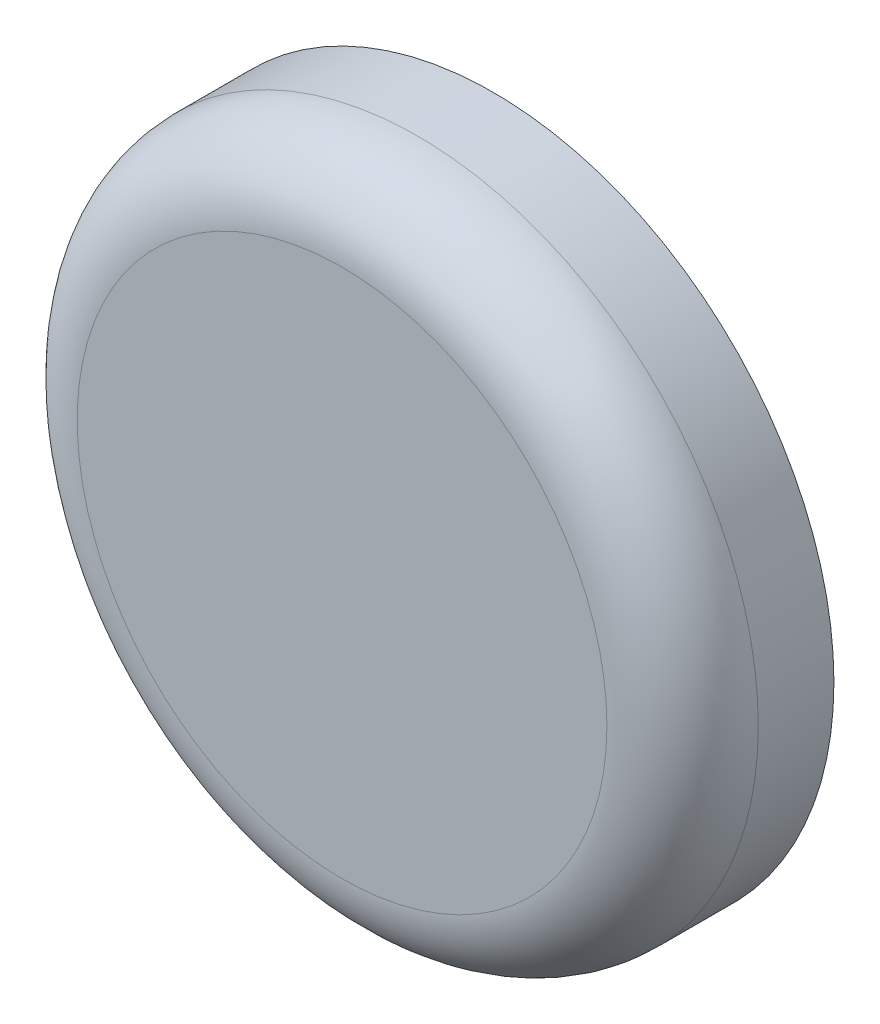
SolidWorks part; units mm, degrees
ref_plane "Спереди" through (0, 0, 0) normal (0, 0, 1) x (1, 0, 0)
ref_plane "Сверху" through (0, 0, 0) normal (0, 1, 0) x (1, 0, 0)
ref_plane "Справа" through (0, 0, 0) normal (1, 0, 0) x (0, 0, -1)
sketch "Эскиз1" plane through (0, 0, 0) normal (0, 0, 1) x (1, 0, 0)
  circle A0 centre (0, 0) radius 4.5
  dimension "D1" = 9
extrude "Бобышка-Вытянуть1" add sketch "Эскиз1" along normal blind 2
fillet "Скругление1" radius 1 1 edges at (4.5, 0, 2)
